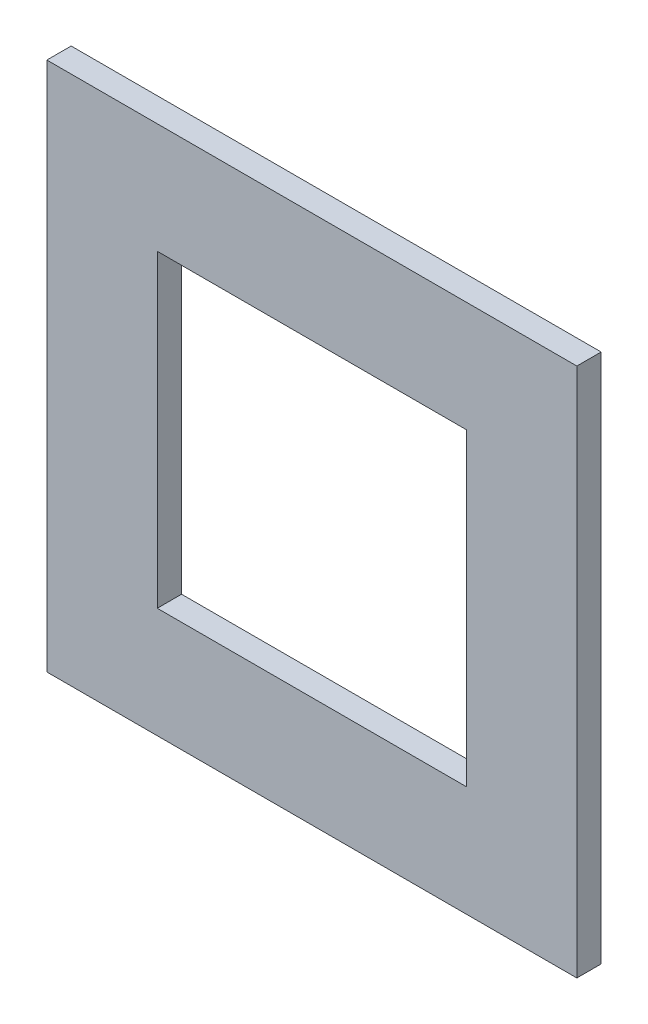
SolidWorks part; units mm, degrees
ref_plane "Front Plane" through (0, 0, 0) normal (0, 0, 1) x (1, 0, 0)
ref_plane "Top Plane" through (0, 0, 0) normal (0, 1, 0) x (1, 0, 0)
ref_plane "Right Plane" through (0, 0, 0) normal (1, 0, 0) x (0, 0, -1)
sketch "Sketch1" plane through (0, 0, 0) normal (0, 0, 1) x (1, 0, 0)
  line L1 (-12, 12) -> (12, 12)
  line L2 (-12, 12) -> (-12, -12)
  line L3 (-12, -12) -> (12, -12)
  line L4 (12, 12) -> (12, -12)
  line L5 (0, -12) -> (0, 12) construction
  line L6 (-12, 0) -> (12, 0) construction
  line L7 (-7, 7) -> (7, 7)
  line L8 (-7, 7) -> (-7, -7)
  line L9 (-7, -7) -> (7, -7)
  line L10 (7, 7) -> (7, -7)
  line L11 (0, -7) -> (0, 7) construction
  line L12 (-7, 0) -> (7, 0) construction
  point P0 (0, 0)
  point P4 (0, 0)
  dimension "D1" = 14
  dimension "D2" = 14
  dimension "D3" = 5
  dimension "D4" = 5
extrude "Boss-Extrude1" add sketch "Sketch1" along normal blind 1.1
